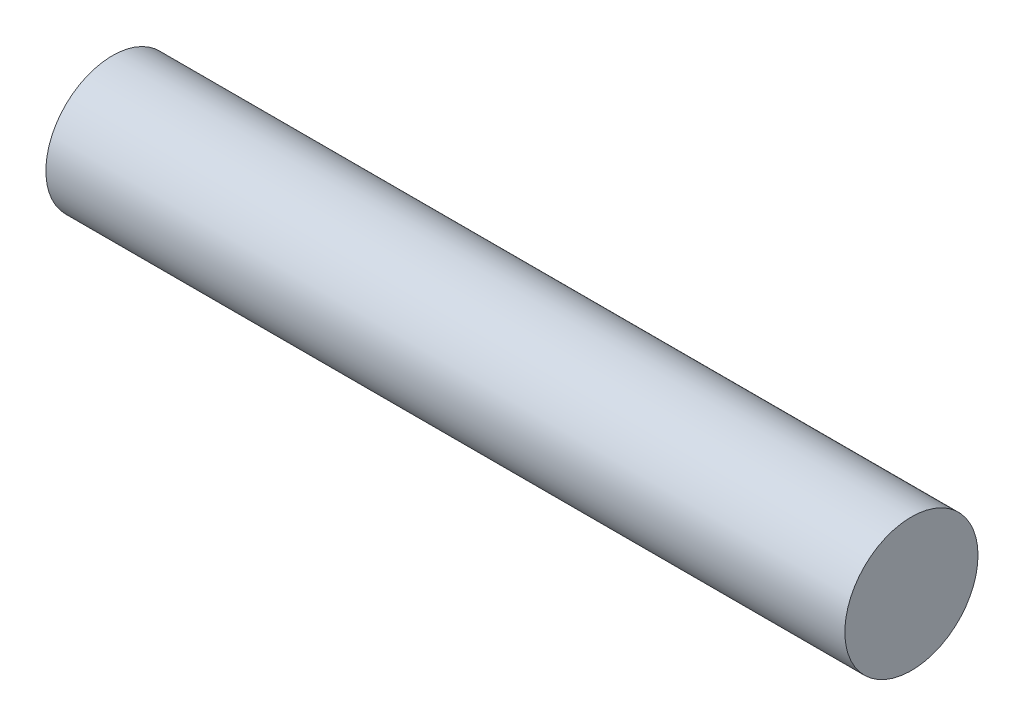
SolidWorks part; units mm, degrees
ref_plane "Front Plane" through (0, 0, 0) normal (0, 0, 1) x (1, 0, 0)
ref_plane "Top Plane" through (0, 0, 0) normal (0, 1, 0) x (1, 0, 0)
ref_plane "Right Plane" through (0, 0, 0) normal (1, 0, 0) x (0, 0, -1)
sketch "Sketch1" plane through (0, 0, 0) normal (1, 0, 0) x (0, 0, -1)
  circle A0 centre (0, 0) radius 15
extrude "Boss-Extrude1" add sketch "Sketch1" against normal blind 180
